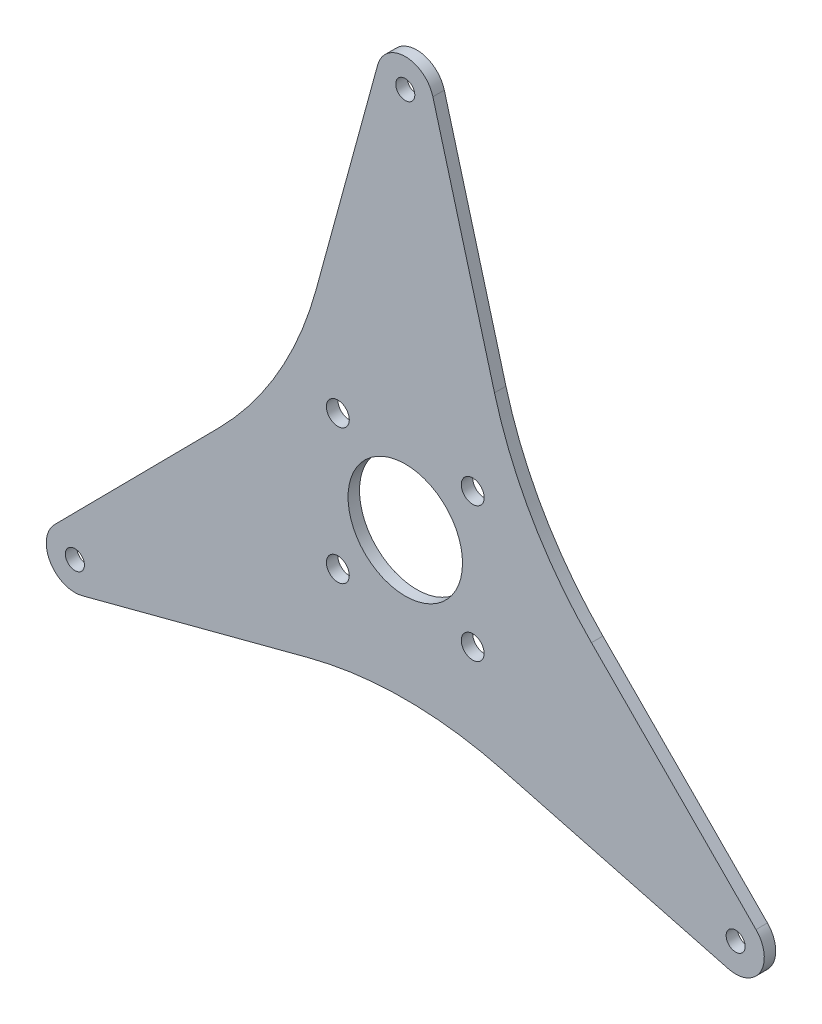
SolidWorks part; units mm, degrees
ref_plane "Front Plane" through (0, 0, 0) normal (0, 0, 1) x (1, 0, 0)
ref_plane "Top Plane" through (0, 0, 0) normal (0, 1, 0) x (1, 0, 0)
ref_plane "Right Plane" through (0, 0, 0) normal (1, 0, 0) x (0, 0, -1)
sketch "Sketch1" plane through (0, 0, 0) normal (0, 0, 1) x (1, 0, 0)
  line L0 (-35.3553, 35.3553) -> (0, 0) construction
  line L1 (0, 0) -> (0, 51.7411) construction
  line L2 (-183.8631, -89.4451) -> (-97.5988, -2.3382)
  line L3 (-46.7745, 85.6921) -> (-14.4698, 203.9527)
  line L4 (14.4698, 203.9527) -> (46.7745, 85.6921)
  line L5 (97.5988, -2.3382) -> (183.8631, -89.4451)
  line L6 (0, 0) -> (-81.3002, 46.9387) construction
  line L7 (-169.3933, -114.5076) -> (-50.8243, -83.3539)
  line L8 (50.8243, -83.3539) -> (169.3933, -114.5076)
  circle A0 centre (0, 200) radius 5
  circle A1 centre (173.2051, -100) radius 5
  circle A2 centre (-173.2051, -100) radius 5
  circle A3 centre (-35.3553, 35.3553) radius 6
  circle A4 centre (35.3553, 35.3553) radius 6
  circle A5 centre (35.3553, -35.3553) radius 6
  circle A6 centre (-35.3553, -35.3553) radius 6
  circle A7 centre (0, 0) radius 30
  arc A8 (14.4698, 203.9527) -> (-14.4698, 203.9527) centre (0, 200) ccw
  arc A9 (169.3933, -114.5076) -> (183.8631, -89.4451) centre (173.2051, -100) ccw
  arc A10 (-183.8631, -89.4451) -> (-169.3933, -114.5076) centre (-173.2051, -100) ccw
  arc A11 (46.7745, 85.6921) -> (97.5988, -2.3382) centre (239.7058, 138.3942) ccw
  arc A12 (-97.5988, -2.3382) -> (-46.7745, 85.6921) centre (-239.7058, 138.3942) ccw
  arc A13 (-50.8243, -83.3539) -> (50.8243, -83.3539) centre (0, -276.7884) cw
  circle A14 centre (0, 0) radius 67 construction
  point P10 (0, 0)
  point P21 (0, 0)
  point P30 (0, -70)
  point P40 (60.6218, 35)
  point P43 (-60.6218, 35)
  dimension "D1" = 10
  dimension "D4" = 50
  dimension "D6" = 12
  dimension "D8" = 60
  dimension "D9" = 30
  dimension "D11" = 200
  dimension "D12" = 200
  dimension "D2" = 200
  dimension "D5" = 45
  dimension "D10" = 60
  dimension "D13" = 70
  dimension "D14" = 70
  dimension "D3" = 3
  dimension "D7" = 4
extrude "Boss-Extrude1" add sketch "Sketch1" along normal blind 6
